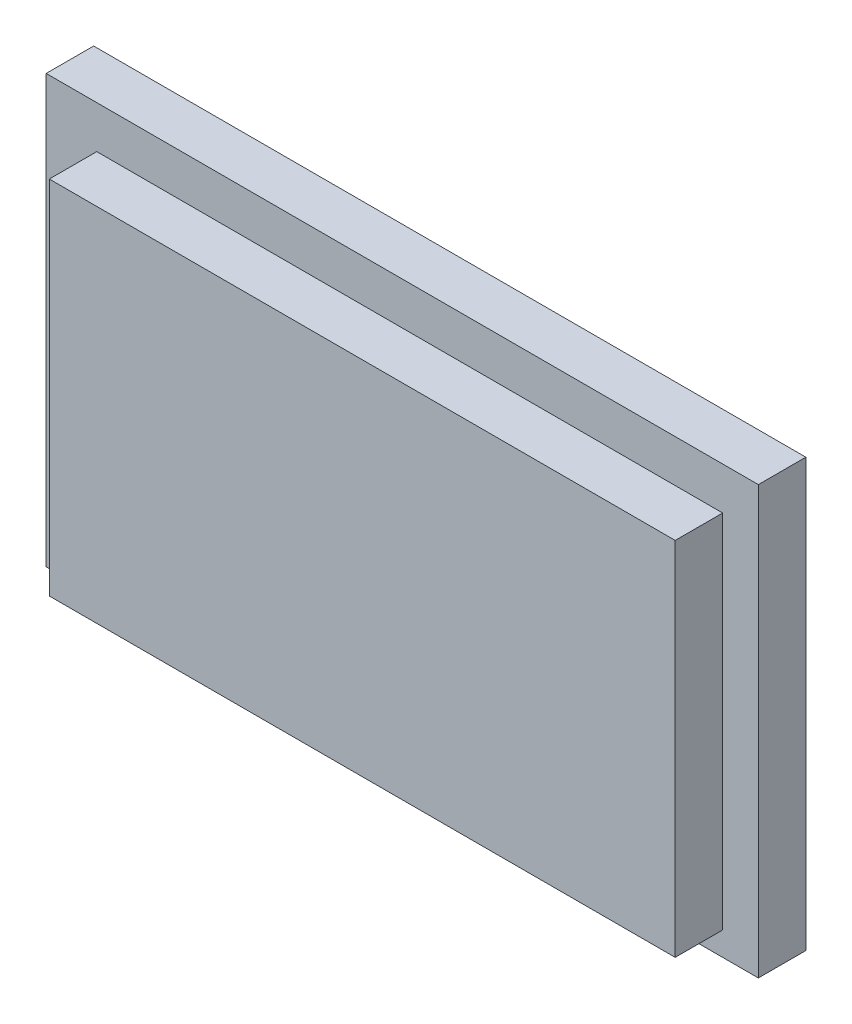
SolidWorks part; units mm, degrees
ref_plane "前视基准面" through (0, 0, 0) normal (0, 0, 1) x (1, 0, 0)
ref_plane "上视基准面" through (0, 0, 0) normal (0, 1, 0) x (1, 0, 0)
ref_plane "右视基准面" through (0, 0, 0) normal (1, 0, 0) x (0, 0, -1)
sketch "草图2" plane through (0, 0, 0) normal (0, 0, 1) x (1, 0, 0)
  line L1 (-16.5978, 10.0675) -> (13.4022, 10.0675)
  line L2 (-16.5978, 10.0675) -> (-16.5978, -7.9325)
  line L3 (-16.5978, -7.9325) -> (13.4022, -7.9325)
  line L4 (13.4022, 10.0675) -> (13.4022, -7.9325)
  dimension "D1" = 30
  dimension "D2" = 18
extrude "凸台-拉伸1" add sketch "草图2" along normal blind 2
sketch "草图3" plane through (0, 0, 2) normal (0, 0, 1) x (1, 0, 0)
  line L1 (-14.4662, 8.2802) -> (11.8993, 8.2802)
  line L2 (-14.4662, 8.2802) -> (-14.4662, -6.9316)
  line L3 (-14.4662, -6.9316) -> (11.8993, -6.9316)
  line L4 (11.8993, 8.2802) -> (11.8993, -6.9316)
extrude "凸台-拉伸2" add sketch "草图3" along normal blind 2
